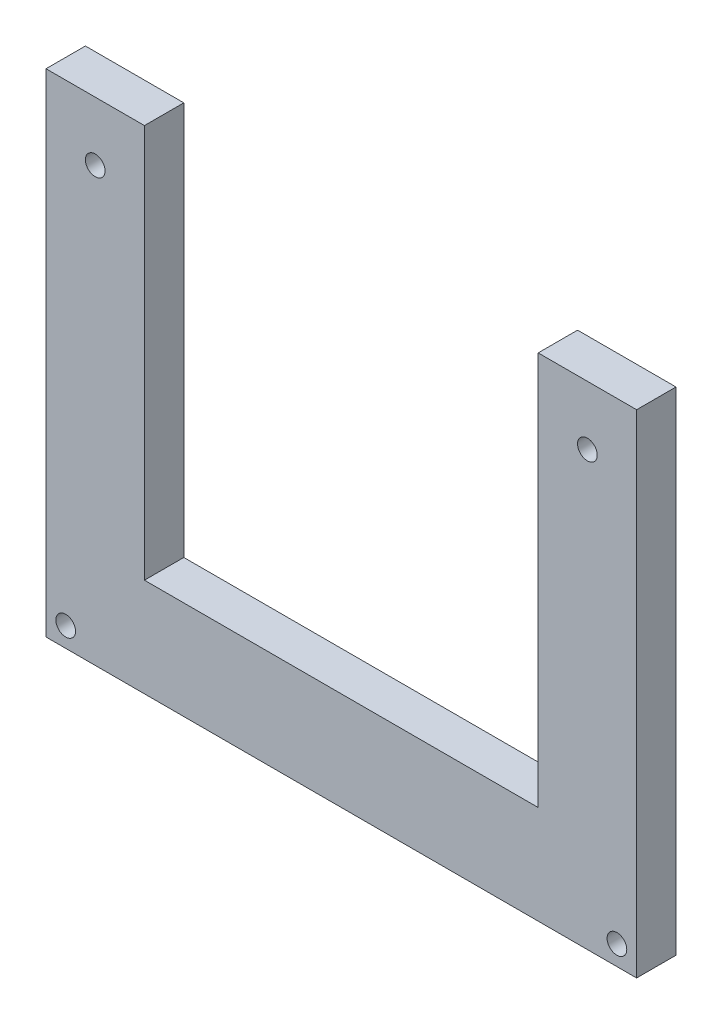
SolidWorks part; units mm, degrees
ref_plane "Front Plane" through (0, 0, 0) normal (0, 0, 1) x (1, 0, 0)
ref_plane "Top Plane" through (0, 0, 0) normal (0, 1, 0) x (1, 0, 0)
ref_plane "Right Plane" through (0, 0, 0) normal (1, 0, 0) x (0, 0, -1)
sketch "Sketch1" plane through (0, 0, 0) normal (0, 0, 1) x (1, 0, 0)
  line L0 (0, 0) -> (0, -250)
  line L1 (0, -250) -> (300, -250)
  line L3 (250, -200) -> (50, -200)
  line L4 (50, -200) -> (50, 0)
  line L5 (50, 0) -> (0, 0)
  line L6 (150, -250) -> (150, -16.6289) construction
  line L7 (250, 0) -> (300, 0)
  line L8 (250, -200) -> (250, 0)
  line L9 (300, 0) -> (300, -250)
  point P10 (150, -200)
  point P12 (250, -100)
  dimension "D1" = 50
  dimension "D2" = 200
  dimension "D3" = 200
  dimension "D4" = 50
extrude "Boss-Extrude1" add sketch "Sketch1" along normal blind 20
sketch "Sketch2" plane through (0, 0, 20) normal (0, 0, 1) x (1, 0, 0)
  line L0 (0, -30) -> (300, -30) construction
  line L1 (0, 0) -> (0, -250) construction
  line L2 (300, -250) -> (300, 0) construction
  line L3 (50, 0) -> (0, 0) construction
  circle A0 centre (25, -30) radius 5
  circle A1 centre (275, -30) radius 5
  dimension "D1" = 10
  dimension "D2" = 10
  dimension "D3" = 30
extrude "Cut-Extrude1" cut sketch "Sketch2" against normal up to next
sketch "Sketch3" plane through (0, 0, 0) normal (0, 0, -1) x (-1, 0, 0)
  line L0 (-150, -250) -> (-150, -200) construction
  line L1 (0, -250) -> (-300, -250) construction
  line L2 (-250, -200) -> (-50, -200) construction
  line L3 (-300, -250) -> (-300, 0) construction
  circle A0 centre (-290, -240) radius 5
  circle A1 centre (-10, -240) radius 5
  dimension "D1" = 10
  dimension "D2" = 10
  dimension "D3" = 10
extrude "Cut-Extrude2" cut sketch "Sketch3" against normal up to next
